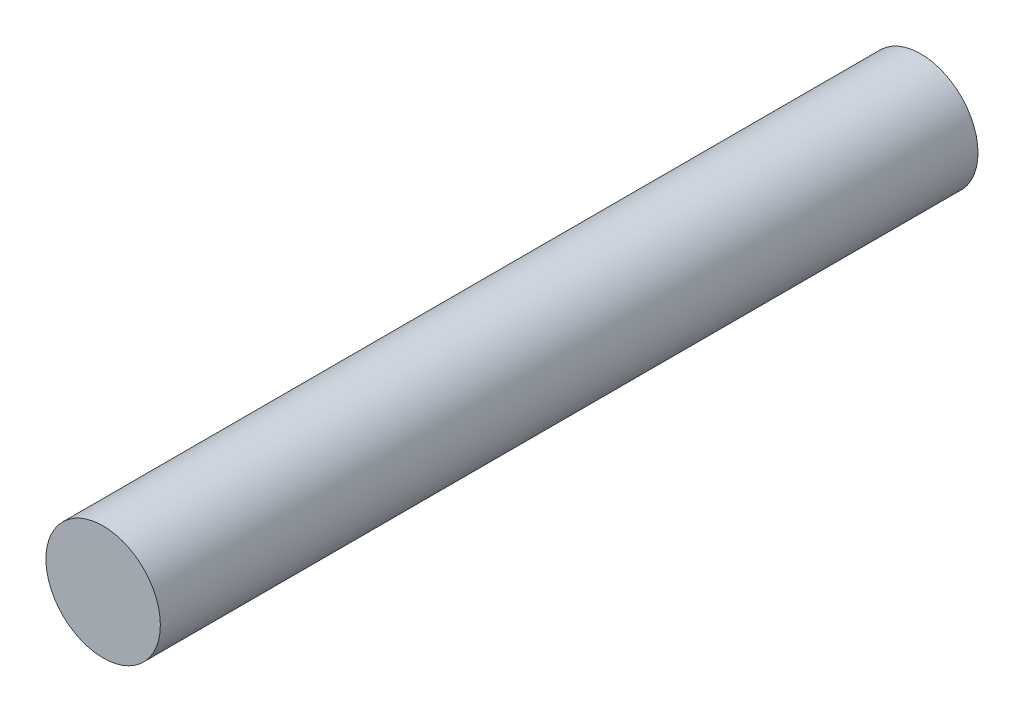
SolidWorks part; units mm, degrees
ref_plane "Front Plane" through (0, 0, 0) normal (0, 0, 1) x (1, 0, 0)
ref_plane "Top Plane" through (0, 0, 0) normal (0, 1, 0) x (1, 0, 0)
ref_plane "Right Plane" through (0, 0, 0) normal (1, 0, 0) x (0, 0, -1)
sketch "Sketch1" plane through (0, 0, 0) normal (0, 0, 1) x (1, 0, 0)
  circle A0 centre (0, 0) radius 7
extrude "Boss-Extrude1" add sketch "Sketch1" along normal blind 100
